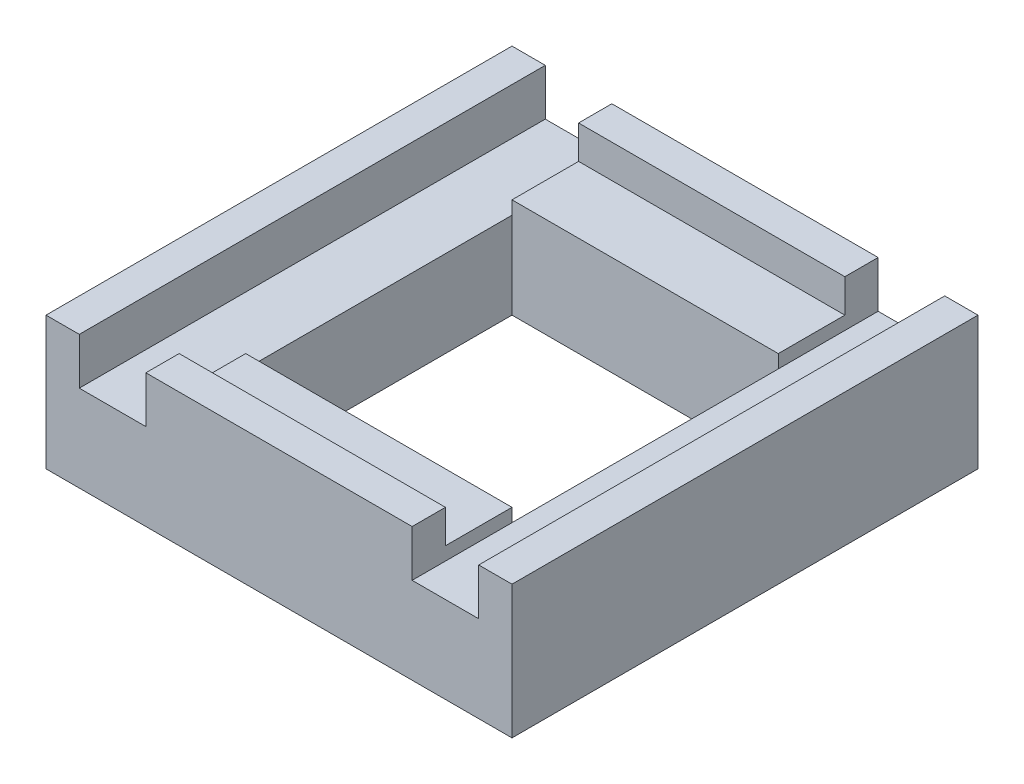
SolidWorks part; units mm, degrees
ref_plane "Alzado" through (0, 0, 0) normal (0, 0, 1) x (1, 0, 0)
ref_plane "Planta" through (0, 0, 0) normal (0, 1, 0) x (1, 0, 0)
ref_plane "Vista lateral" through (0, 0, 0) normal (1, 0, 0) x (0, 0, -1)
sketch "Croquis1" plane through (0, 0, 0) normal (0, 1, 0) x (1, 0, 0)
  line L1 (0, 0) -> (70, 0)
  line L2 (0, 0) -> (0, 70)
  line L3 (0, 70) -> (70, 70)
  line L4 (70, 0) -> (70, 70)
  dimension "D1" = 70
extrude "Saliente-Extruir1" add sketch "Croquis1" along normal blind 20
sketch "Croquis2" plane through (0, 20, 0) normal (0, 1, 0) x (1, 0, 0)
  line L8 (5, 65) -> (5, 5)
  line L9 (5, 5) -> (65, 5)
  line L10 (65, 5) -> (65, 65)
  line L11 (65, 65) -> (5, 65)
  line L12 (5, 65) -> (5, 5)
  line L13 (5, 5) -> (65, 5)
  line L14 (65, 5) -> (65, 65)
  line L15 (65, 65) -> (5, 65)
  dimension "D1" = 5
extrude "Cortar-Extruir1" cut sketch "Croquis2" against normal blind 5
sketch "Croquis3" plane through (0, 15, 0) normal (0, 1, 0) x (1, 0, 0)
  line L0 (0, 0) -> (70, 0) construction
  line L1 (5, 0) -> (15, 0)
  line L2 (5, 0) -> (5, 70)
  line L3 (5, 70) -> (15, 70)
  line L4 (15, 0) -> (15, 70)
  line L5 (70, 70) -> (0, 70) construction
  line L6 (5, 65) -> (5, 5) construction
  line L7 (35, 5) -> (35, 65) construction
  line L8 (5, 5) -> (65, 5) construction
  line L9 (65, 65) -> (5, 65) construction
  line L10 (65, 70) -> (55, 70)
  line L11 (55, 0) -> (55, 70)
  line L12 (65, 0) -> (55, 0)
  line L13 (65, 0) -> (65, 70)
  dimension "D1" = 20
extrude "Cortar-Extruir2" cut sketch "Croquis3" against normal blind 2 and the other way blind 5
sketch "Croquis4" plane through (0, 15, 0) normal (0, 1, 0) x (1, 0, 0)
  line L0 (15, 65) -> (15, 5) construction
  line L1 (15, 15) -> (55, 15)
  line L2 (15, 15) -> (15, 55)
  line L3 (15, 55) -> (55, 55)
  line L4 (55, 15) -> (55, 55)
  line L5 (55, 5) -> (55, 65) construction
  line L6 (55, 35) -> (70, 35) construction
  line L7 (70, 0) -> (70, 70) construction
extrude "Cortar-Extruir3" cut sketch "Croquis4" against normal blind 52
